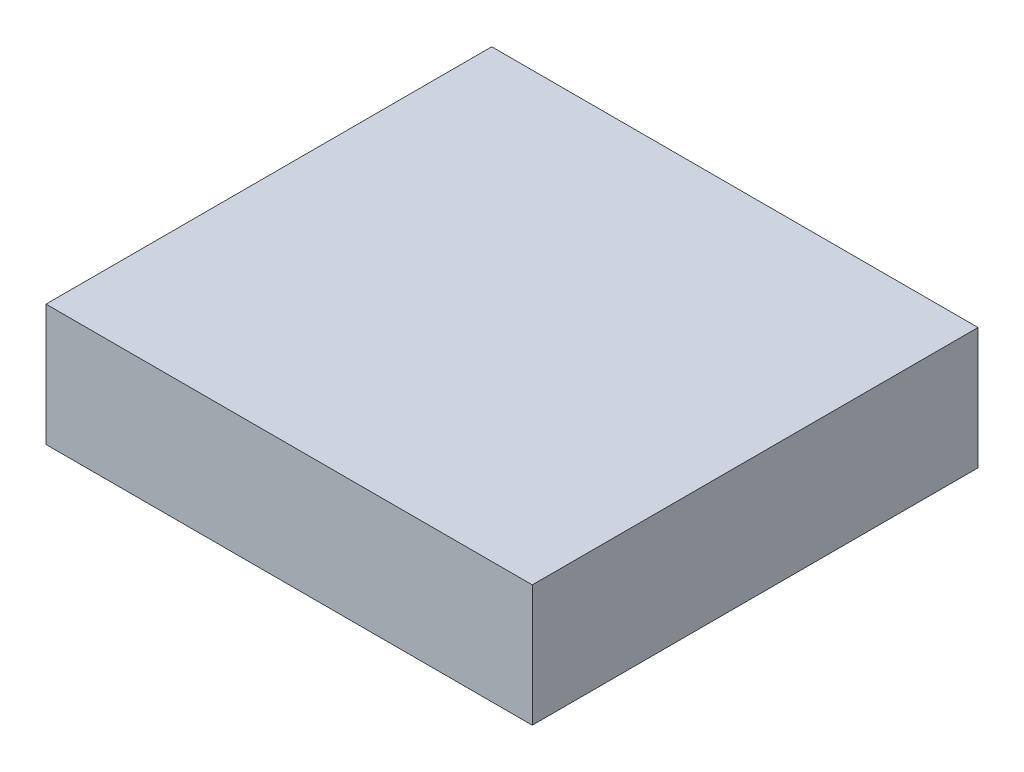
SolidWorks part; units mm, degrees
material "Low Carbon Steel"
ref_plane "Front Plane" through (0, 0, 0) normal (0, 0, 1) x (1, 0, 0)
ref_plane "Top Plane" through (0, 0, 0) normal (0, 1, 0) x (1, 0, 0)
ref_plane "Right Plane" through (0, 0, 0) normal (1, 0, 0) x (0, 0, -1)
sketch "Sketch1" plane through (0, 0, 0) normal (0, 1, 0) x (1, 0, 0)
  line L0 (-76.2, -69.85) -> (76.2, 69.85) construction
  line L1 (-76.2, 69.85) -> (76.2, 69.85)
  line L2 (-76.2, 69.85) -> (-76.2, -69.85)
  line L3 (-76.2, -69.85) -> (76.2, -69.85)
  line L4 (76.2, 69.85) -> (76.2, -69.85)
  dimension "D1" = 152.4
  dimension "D2" = 139.7
extrude "Boss-Extrude1" add sketch "Sketch1" along normal blind 38.1
other "Freeze***"
equation "\"4.50inn\"=4.5"
